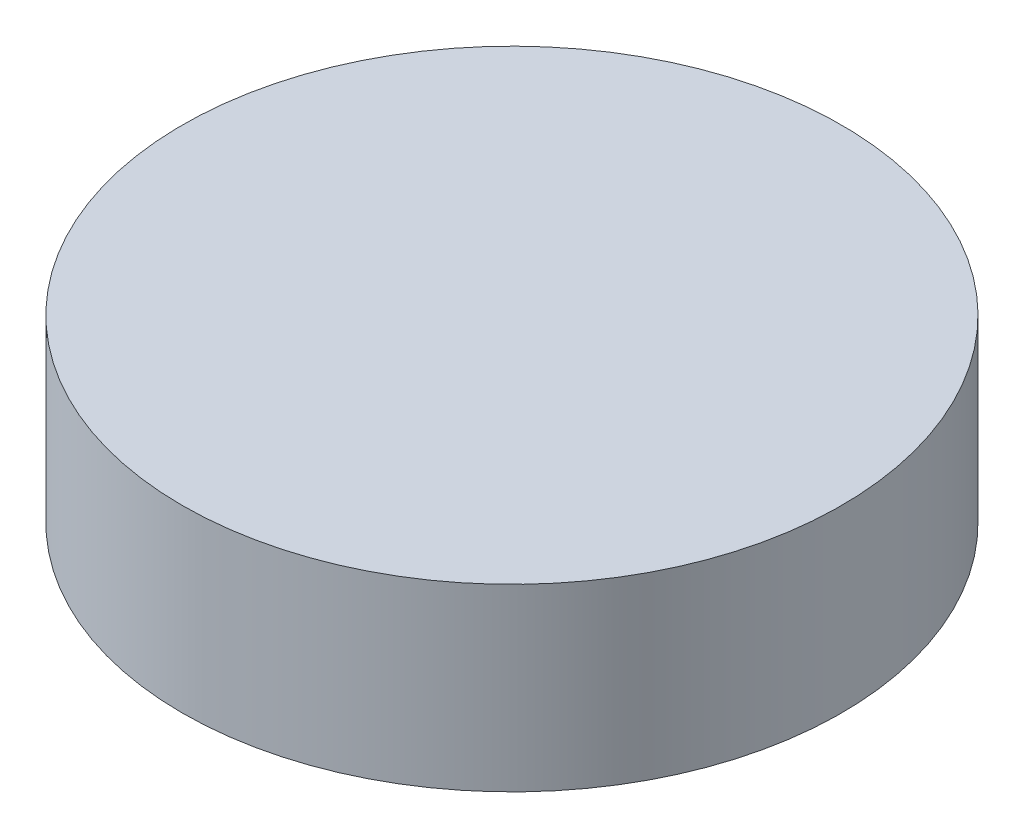
SolidWorks part; units mm, degrees
ref_plane "前视基准面" through (0, 0, 0) normal (0, 0, 1) x (1, 0, 0)
ref_plane "上视基准面" through (0, 0, 0) normal (0, 1, 0) x (1, 0, 0)
ref_plane "右视基准面" through (0, 0, 0) normal (1, 0, 0) x (0, 0, -1)
other "Configuration Table"
sketch "草图1" plane through (0, 0, 0) normal (0, 1, 0) x (1, 0, 0)
  circle A0 centre (0, 0) radius 5.5
  dimension "D1" = 11
extrude "凸台-拉伸1" add sketch "草图1" along normal blind 3
sketch "草图2" plane through (0, 0, 0) normal (0, -1, 0) x (1, 0, 0)
  circle A0 centre (0, 0) radius 2.5
  dimension "D1" = 5
extrude "切除-拉伸1" cut sketch "草图2" against normal blind 2 contours A0
